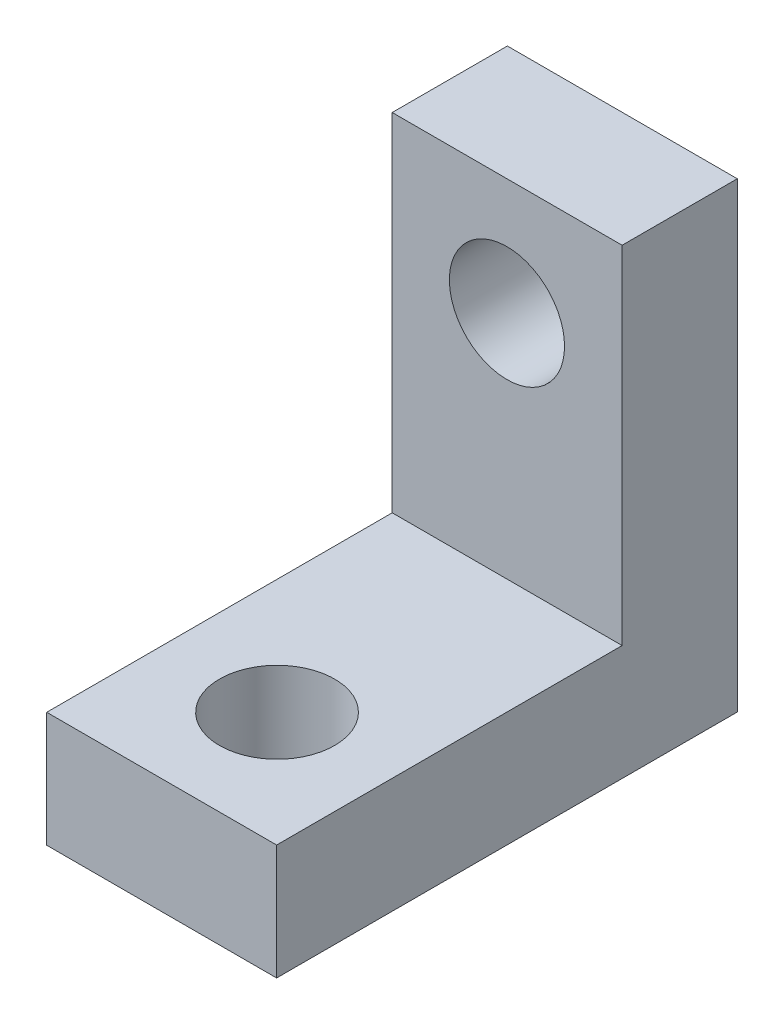
SolidWorks part; units mm, degrees
ref_plane "Front Plane" through (0, 0, 0) normal (0, 0, 1) x (1, 0, 0)
ref_plane "Top Plane" through (0, 0, 0) normal (0, 1, 0) x (1, 0, 0)
ref_plane "Right Plane" through (0, 0, 0) normal (1, 0, 0) x (0, 0, -1)
sketch "Sketch1" plane through (0, 0, 0) normal (0, 0, 1) x (1, 0, 0)
  line L0 (-6.3269, 0) -> (-6.3269, -19.05)
  line L1 (-6.3269, -19.05) -> (6.35, -19.05)
  line L2 (6.35, -19.05) -> (6.35, 0)
  line L3 (-6.3269, 0) -> (-6.3269, 6.4156)
  line L4 (-6.3269, 6.4156) -> (6.35, 6.4156)
  line L5 (6.35, 6.4156) -> (6.35, 0)
  circle A1 centre (0, 0) radius 3.175
  dimension "D2" = 6.35
  dimension "D3" = 19.05
extrude "Boss-Extrude1" add sketch "Sketch1" along normal blind 6.35
sketch "Sketch2" plane through (0, 0, 6.35) normal (0, 0, 1) x (1, 0, 0)
  line L0 (6.35, -19.05) -> (6.35, 6.4156) construction
  line L1 (-6.3269, -19.05) -> (6.35, -19.05)
  line L2 (-6.3269, -19.05) -> (-6.3269, -12.7)
  line L3 (-6.3269, -12.7) -> (6.35, -12.7)
  line L4 (6.35, -19.05) -> (6.35, -12.7)
  dimension "D1" = 6.35
extrude "Boss-Extrude2" add sketch "Sketch2" along normal blind 19.05
sketch "Sketch3" plane through (0, -12.7, 0) normal (0, 1, 0) x (1, 0, 0)
  line L0 (-6.3269, -25.4) -> (-6.3269, -6.35) construction
  line L1 (6.35, -25.4) -> (-6.3269, -25.4) construction
  circle A0 centre (0.0231, -19.05) radius 3.175
  dimension "D1" = 6.35
  dimension "D2" = 6.35
  dimension "D3" = 6.35
extrude "Cut-Extrude1" cut sketch "Sketch3" against normal blind 19.05
